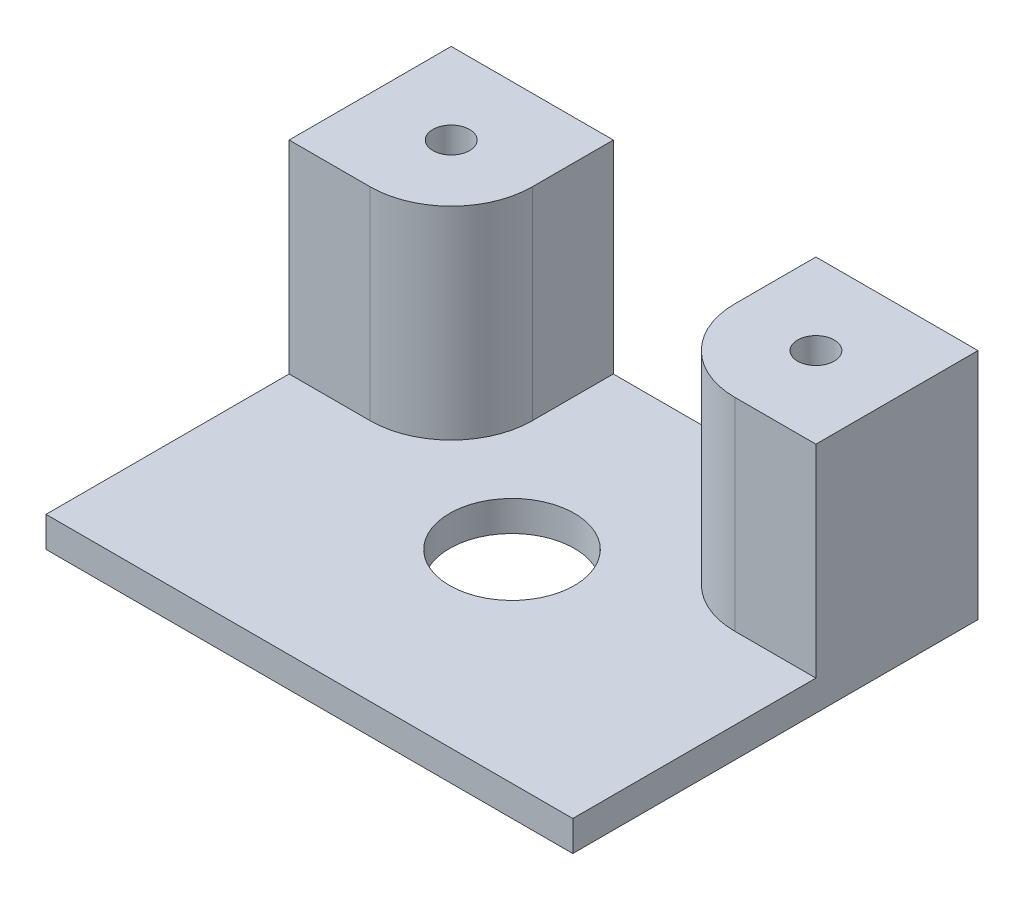
SolidWorks part; units mm, degrees
material "AISI 1020"
ref_plane "Front Plane" through (0, 0, 0) normal (0, 0, 1) x (1, 0, 0)
ref_plane "Top Plane" through (0, 0, 0) normal (0, 1, 0) x (1, 0, 0)
ref_plane "Right Plane" through (0, 0, 0) normal (1, 0, 0) x (0, 0, -1)
sketch "Sketch1" plane through (0, 0, 0) normal (0, 1, 0) x (1, 0, 0)
  line L1 (0, 0) -> (165.1, 0)
  line L2 (0, 0) -> (0, 127)
  line L3 (0, 127) -> (165.1, 127)
  line L4 (165.1, 0) -> (165.1, 127)
  dimension "D1" = 165.1
  dimension "D2" = 127
extrude "Boss-Extrude1" add sketch "Sketch1" along normal blind 9.525
sketch "Sketch2" plane through (0, 9.525, 0) normal (0, 1, 0) x (1, 0, 0)
  line L1 (165.1, 127) -> (0, 127) construction
  line L3 (165.1, 0) -> (165.1, 127) construction
  circle A0 centre (82.55, 63.5) radius 19.5794
  point P2 (0, 0)
  point P7 (0, 0)
  dimension "D1" = 63.5
  dimension "D2" = 82.55
extrude "Cut-Extrude1" cut sketch "Sketch2" against normal through all
sketch "Sketch3" plane through (0, 9.525, 0) normal (0, 1, 0) x (1, 0, 0)
  line L0 (0, 101.6) -> (50.8, 101.6) construction
  line L1 (0, 127) -> (50.8, 127)
  line L2 (0, 127) -> (0, 76.2)
  line L3 (0, 76.2) -> (25.4, 76.2)
  line L4 (50.8, 127) -> (50.8, 101.6)
  line L5 (165.1, 127) -> (114.3, 127)
  line L6 (165.1, 127) -> (165.1, 76.2)
  line L7 (165.1, 76.2) -> (139.7, 76.2)
  line L8 (114.3, 127) -> (114.3, 101.6)
  line L9 (114.3, 101.6) -> (165.1, 101.6) construction
  arc A0 (50.8, 101.6) -> (25.4, 76.2) centre (25.4, 101.6) cw
  arc A1 (114.3, 101.6) -> (139.7, 76.2) centre (139.7, 101.6) ccw
  dimension "D1" = 50.8
  dimension "D2" = 50.8
  dimension "D3" = 50.8
  dimension "D4" = 50.8
extrude "Boss-Extrude3" add sketch "Sketch3" along normal blind 63.5
hole_wizard "1/2-20 Tapped Hole1" positions "3DSketch2" profile "Sketch6" tap size "1/2-20" standard "ANSI Inch"
sketch3d "3DSketch2"
  line L1 (25.4, 73.025, -101.6) -> (25.4, 73.025, -127) construction
  line L2 (50.8, 73.025, -127) -> (0, 73.025, -127) construction
  line L4 (139.7, 73.025, -101.6) -> (139.7, 73.025, -127) construction
  line L5 (165.1, 73.025, -127) -> (114.3, 73.025, -127) construction
  point P0 (25.4, 73.025, -101.6)
  point P2 (139.7, 73.025, -101.6)
  dimension "D1" = 25.4
  dimension "D2" = 25.4
sketch "Sketch6" plane through (25.4, 73.025, -101.6) normal (1, 0, 0) x (0, 0, 1)
  line L0 (0, 0) -> (0, 35.2076)
  line L1 (0, 35.2076) -> (5.7544, 31.75)
  line L2 (5.7544, 31.75) -> (5.7544, 0)
  line L5 (5.7544, 0) -> (0, 0)
  line L10 (0, 35.2076) -> (-5.7544, 31.75) construction
  line L11 (0, -6.35) -> (0, 107.95) construction
  dimension "Tap Drill Dia." = 11.5087
  dimension "Tap Drill Depth" = 31.75
  dimension "Drill Angle" = 118
cosmetic thread "Hole Thread2"
cosmetic thread "Hole Thread3"
